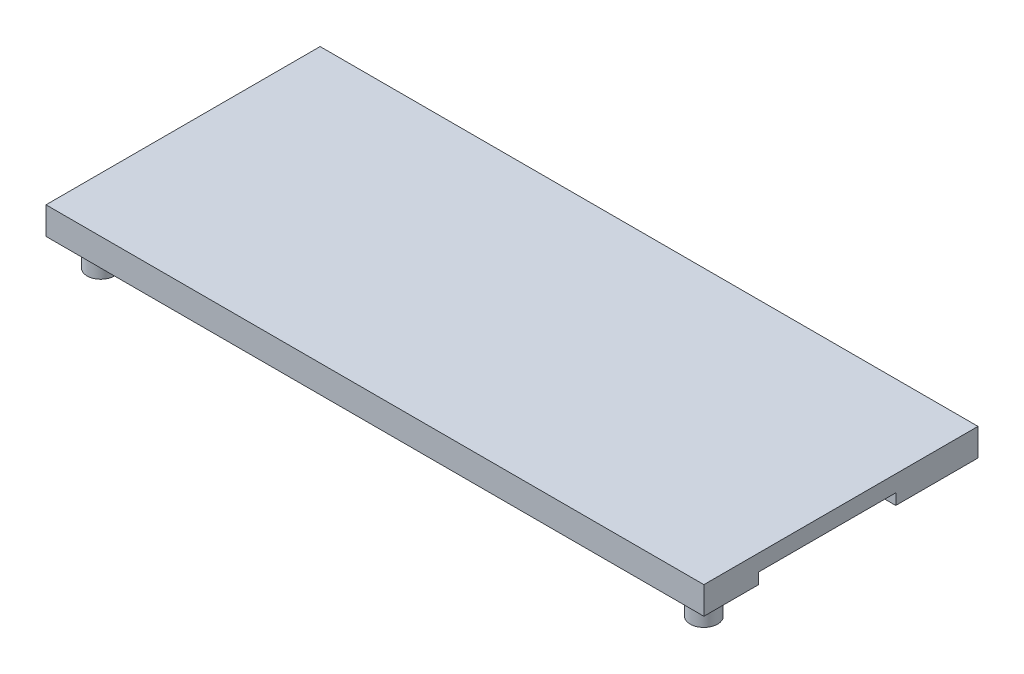
SolidWorks part; units mm, degrees
ref_plane "Front Plane" through (0, 0, 0) normal (0, 0, 1) x (1, 0, 0)
ref_plane "Top Plane" through (0, 0, 0) normal (0, 1, 0) x (1, 0, 0)
ref_plane "Right Plane" through (0, 0, 0) normal (1, 0, 0) x (0, 0, -1)
sketch "Sketch1" plane through (0, 0, 0) normal (0, 1, 0) x (1, 0, 0)
  line L1 (-51.8537, 0) -> (68.1463, 0)
  line L2 (-51.8537, 0) -> (-51.8537, 50)
  line L3 (-51.8537, 50) -> (68.1463, 50)
  line L4 (68.1463, 0) -> (68.1463, 50)
  dimension "D1" = 120
  dimension "D2" = 50
extrude "Boss-Extrude1" add sketch "Sketch1" along normal blind 5
sketch "Sketch2" plane through (68.1463, 0, 0) normal (1, 0, 0) x (0, 0, -1)
  line L0 (0, 5) -> (0, 0) construction
  line L1 (10, 2) -> (35, 2)
  line L2 (10, 2) -> (10, 0)
  line L4 (35, 2) -> (35, 0)
  dimension "D1" = 2
  dimension "D2" = 25
  dimension "D3" = 10
extrude "Cut-Extrude1" cut sketch "Sketch2" against normal blind 120 and the other way through all
sketch "Sketch5" plane through (0, 0, -10) normal (0, 0, -1) x (-1, 0, 0)
  line L5 (-44.1484, 0) -> (-46.1484, 2)
  line L7 (-68.1463, 0) -> (51.8537, 0) construction
  line L8 (-68.1463, 2) -> (51.8537, 2) construction
  line L9 (-46.1484, 2) -> (-44.1484, 2)
  line L10 (-44.1484, 2) -> (-44.1484, 0)
  dimension "D1" = 2
extrude "Boss-Extrude2" add sketch "Sketch5" along normal blind 0.75
sketch "Sketch6" plane through (0, 0, -10) normal (0, 0, -1) x (-1, 0, 0)
  line L0 (-20.1783, 0) -> (-20.1783, 2)
  line L2 (-44.1484, 2) -> (51.8537, 2) construction
  line L3 (-20.1783, 2) -> (-22.1783, 2)
  line L4 (-22.1783, 2) -> (-20.1783, 0)
  dimension "D1" = 2
extrude "Boss-Extrude3" add sketch "Sketch6" along normal blind 3.8
sketch "Sketch7" plane through (0, 0, -10) normal (0, 0, -1) x (-1, 0, 0)
  line L0 (3.8533, 0) -> (3.8533, 2)
  line L2 (3.8533, 2) -> (1.8533, 2)
  line L3 (-20.1783, 2) -> (51.8537, 2) construction
  line L4 (1.8533, 2) -> (3.8533, 0)
  dimension "D1" = 2
  dimension "D2" = 2
extrude "Boss-Extrude4" add sketch "Sketch7" along normal blind 5.95
sketch "Sketch9" plane through (0, 0, -10) normal (0, 0, -1) x (-1, 0, 0)
  line L0 (27.8496, 0) -> (27.8535, 2)
  line L2 (3.8533, 2) -> (51.8537, 2) construction
  line L3 (27.8535, 2) -> (25.8535, 2)
  line L4 (25.8535, 2) -> (27.8496, 0)
  dimension "D1" = 2
extrude "Boss-Extrude6" add sketch "Sketch9" along normal blind 7.1
sketch "Sketch10" plane through (0, 0, 0) normal (0, -1, 0) x (1, 0, 0)
  line L0 (-51.8537, -10) -> (-51.8537, 0) construction
  line L2 (-51.8537, 0) -> (68.1463, 0) construction
  line L3 (68.1463, 0) -> (68.1463, -10) construction
  circle A0 centre (-46.8537, -5) radius 2.5
  circle A1 centre (63.1463, -5) radius 2.5
  dimension "D1" = 5
  dimension "D2" = 5
  dimension "D3" = 5
  dimension "D4" = 5
  dimension "D5" = 5
  dimension "D6" = 5
extrude "Boss-Extrude7" add sketch "Sketch10" along normal blind 5
sketch "Sketch11" plane through (0, 0, -10) normal (0, 0, -1) x (-1, 0, 0)
  line L12 (49.3979, 0) -> (49.3979, 2)
  line L13 (27.8496, 0) -> (51.8537, 0) construction
  line L14 (27.8535, 2) -> (51.8537, 2) construction
  line L15 (49.3979, 2) -> (46.1699, 2)
  line L16 (46.1699, 2) -> (49.3979, 0)
extrude "Boss-Extrude8" add sketch "Sketch11" along normal blind 25
sketch "Sketch12" plane through (0, 0, -10) normal (0, 0, -1) x (-1, 0, 0)
  line L1 (49.3979, 2) -> (51.8537, 2)
  line L2 (49.3979, 2) -> (49.3979, 0)
  line L3 (49.3979, 0) -> (51.8537, 0)
  line L4 (51.8537, 2) -> (51.8537, 0)
extrude "Boss-Extrude9" add sketch "Sketch12" along normal blind 25
fillet "Fillet1" radius 4 5 edges at (46.1484, 2, -10.375) (22.1783, 2, -11.9) (-1.8533, 2, -12.975) (-25.8535, 2, -13.55) (-46.1699, 2, -22.5)
